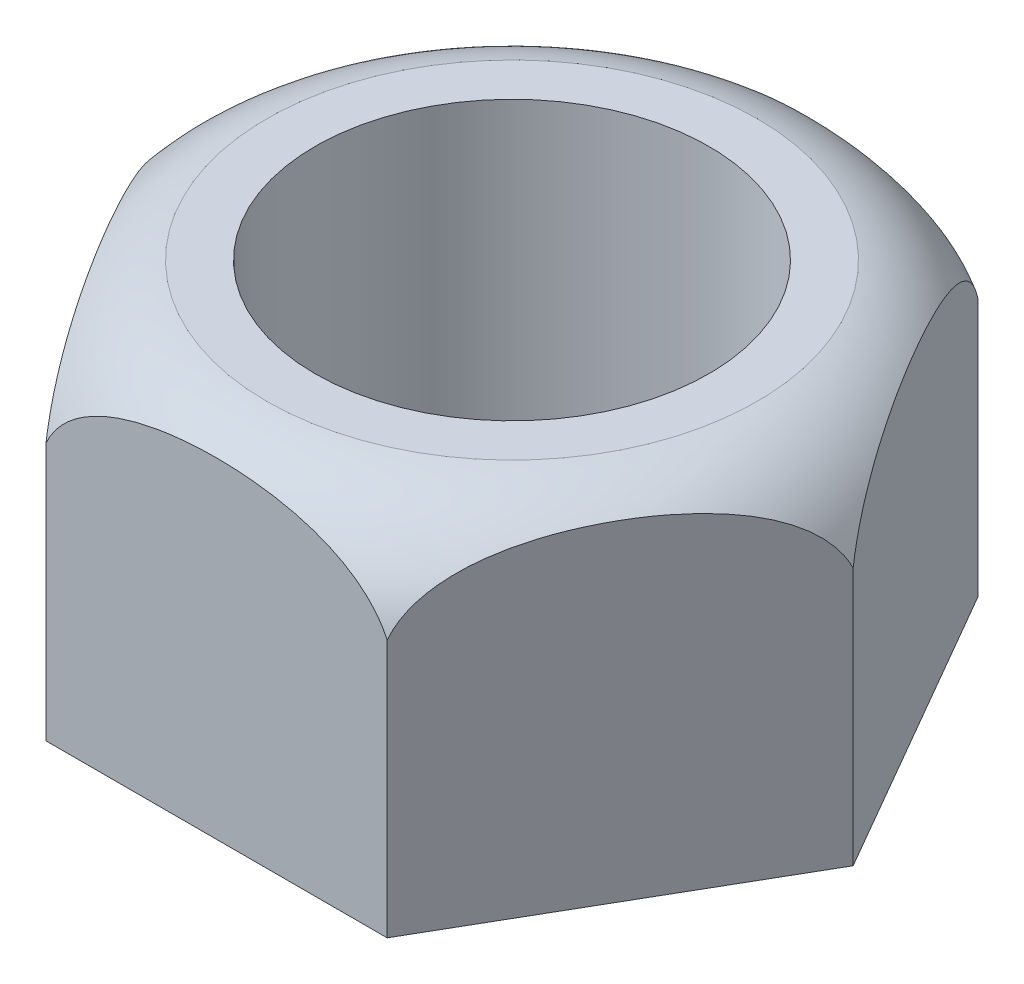
SolidWorks part; units mm, degrees
material "Acier allié"
ref_plane "Face" through (0, 0, 0) normal (0, 0, 1) x (1, 0, 0)
ref_plane "Dessus" through (0, 0, 0) normal (0, 1, 0) x (1, 0, 0)
ref_plane "Droite" through (0, 0, 0) normal (1, 0, 0) x (0, 0, -1)
sketch "Esquisse1" plane through (0, 0, 0) normal (0, 1, 0) x (1, 0, 0)
  line L1 (4.1244, 7.1438) -> (-4.1244, 7.1437)
  line L2 (-4.1244, 7.1437) -> (-8.2489, 0)
  line L3 (-8.2489, 0) -> (-4.1244, -7.1438)
  line L4 (-4.1244, -7.1438) -> (4.1244, -7.1438)
  line L5 (4.1244, -7.1438) -> (8.2489, 0)
  line L6 (8.2489, 0) -> (4.1244, 7.1438)
  circle A0 centre (0, 0) radius 7.1438 construction
  dimension "D1" = 14.2875
extrude "Boss.-Extru.1" add sketch "Esquisse1" along normal blind 8.5598
sketch "Esquisse2" plane through (0, 8.5598, 0) normal (0, 1, 0) x (1, 0, 0)
  circle A0 centre (0, 0) radius 4.7625
  dimension "D1" = 9.525
extrude "Enlèv. mat.-Extru.1" cut sketch "Esquisse2" against normal through all
cosmetic thread "Représentation de filetage1" parameters "D2"=9.5504
sketch "Esquisse6" plane through (0, 0, 0) normal (0, 0, 1) x (1, 0, 0)
  line L0 (0, 0) -> (0, 8.5598) construction
  line L1 (-4.1244, 8.5598) -> (4.1244, 8.5598) construction
  line L2 (0, 8.5598) -> (-4.7625, 8.5598) construction
  line L3 (-4.7625, 8.5598) -> (-4.7625, 0) construction
  line L4 (-4.7625, 8.5598) -> (-5.9246, 8.5598) construction
  line L5 (-8.2489, 8.5598) -> (-4.1244, 8.5598) construction
  line L6 (-8.2489, 8.5598) -> (-8.2489, 0) construction
  line L7 (-8.2489, 8.5598) -> (-7.0868, 8.5598)
  line L8 (-7.0868, 8.5598) -> (-5.9246, 8.5598)
  line L9 (-8.2489, 8.5598) -> (-8.2489, 7.3977)
  line L10 (-8.2489, 7.3977) -> (-8.2489, 6.2355)
  line L12 (-8.2489, 8.5598) -> (-7.4271, 7.738) construction
  arc A0 (-5.9246, 8.5598) -> (-8.2489, 6.2355) centre (-5.2731, 5.584) ccw
revolve "Enlèvement de matière-Révolution1" cut sketch "Esquisse6" angle 360 about L0
equation "\"W\"=9/16"
equation "\"D1@Esquisse1\"=\"W\""
equation "\"H\"=0.337"
equation "\"D1@Boss.-Extru.1\"=\"H\""
equation "\"D\"=3/8"
equation "\"D1@Esquisse2\"=\"D\""
equation "\"D2@Représentation de filetage1\"=\"D\"+0.001"
